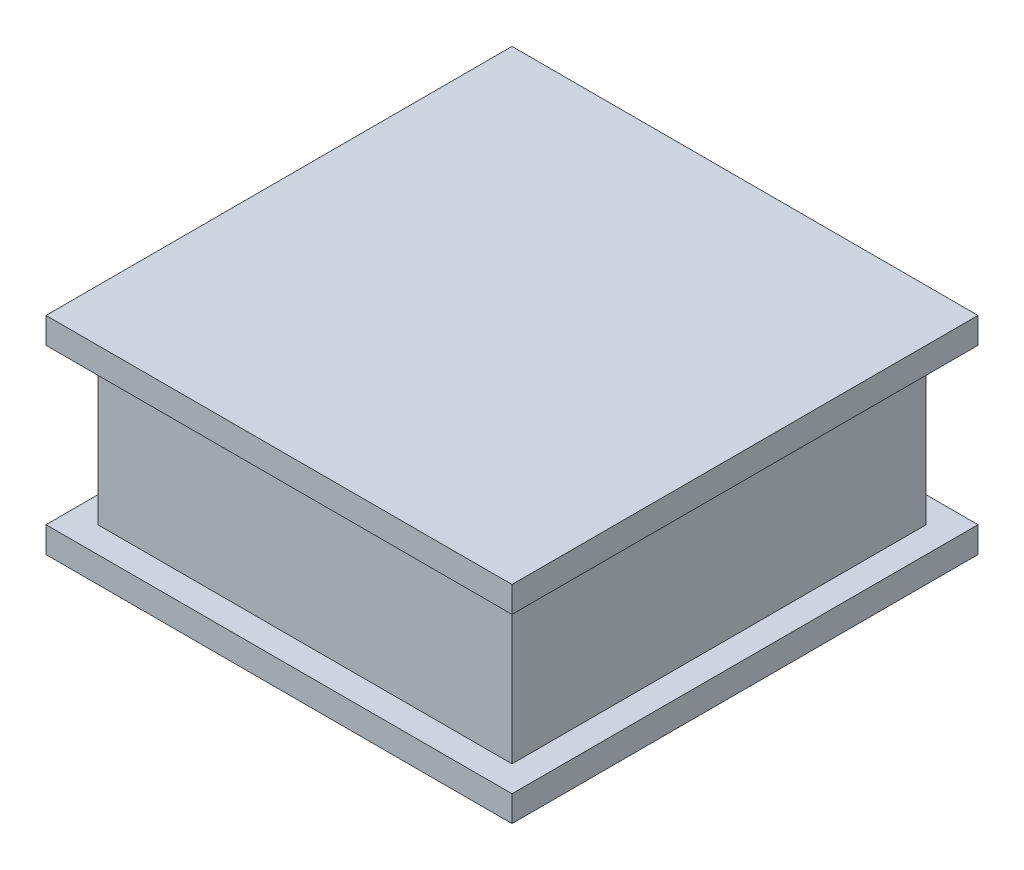
SolidWorks part; units mm, degrees
ref_plane "Спереди" through (0, 0, 0) normal (0, 0, 1) x (1, 0, 0)
ref_plane "Сверху" through (0, 0, 0) normal (0, 1, 0) x (1, 0, 0)
ref_plane "Справа" through (0, 0, 0) normal (1, 0, 0) x (0, 0, -1)
sketch "Эскиз1" plane through (0, 0, 0) normal (0, 1, 0) x (1, 0, 0)
  line L1 (-8, -8) -> (8, -8)
  line L2 (-8, -8) -> (-8, 8)
  line L3 (-8, 8) -> (8, 8)
  line L4 (8, -8) -> (8, 8)
  line L5 (-8, -8) -> (8, 8) construction
  line L6 (-8, 8) -> (8, -8) construction
  point P0 (0, 0)
  dimension "D1" = 16
extrude "Бобышка-Вытянуть1" add sketch "Эскиз1" along normal mid plane 6
sketch "Эскиз2" plane through (0, 3, 0) normal (0, 1, 0) x (1, 0, 0)
  line L0 (8, 8) -> (-8, 8) construction
  line L1 (-9, -9) -> (9, -9)
  line L2 (-9, -9) -> (-9, 9)
  line L3 (-9, 9) -> (9, 9)
  line L4 (9, -9) -> (9, 9)
  line L5 (-9, -9) -> (9, 9) construction
  line L6 (-9, 9) -> (9, -9) construction
  point P0 (0, 0)
  dimension "D1" = 1
extrude "Бобышка-Вытянуть2" add sketch "Эскиз2" along normal blind 1
mirror "Зеркальное отражение1" about plane through (0, 0, 0) normal (0, 1, 0) of "Бобышка-Вытянуть2"
